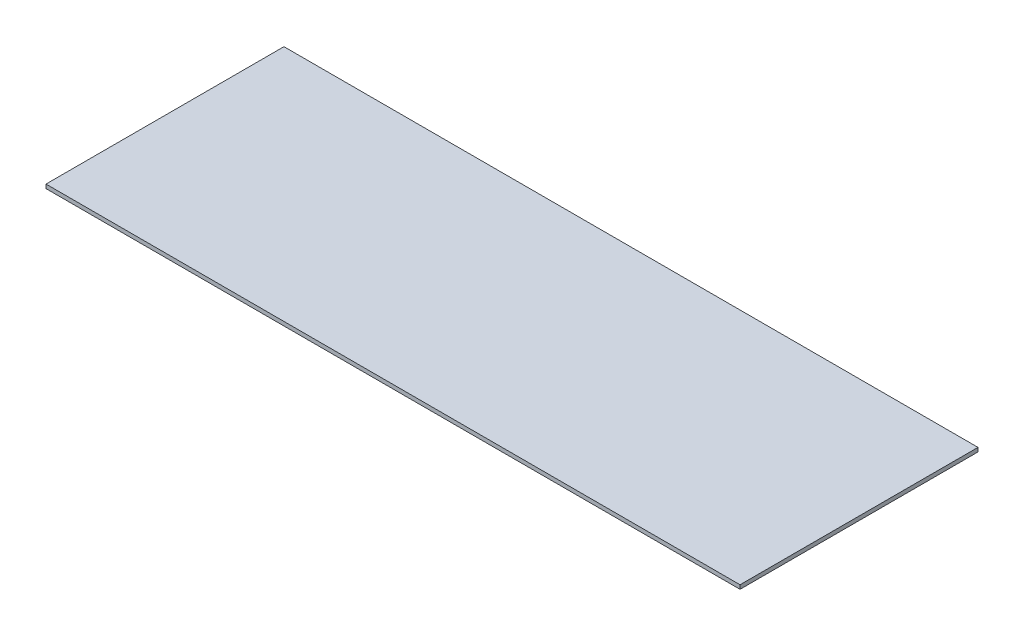
SolidWorks part; units mm, degrees
ref_plane "前视基准面" through (0, 0, 0) normal (0, 0, 1) x (1, 0, 0)
ref_plane "上视基准面" through (0, 0, 0) normal (0, 1, 0) x (1, 0, 0)
ref_plane "右视基准面" through (0, 0, 0) normal (1, 0, 0) x (0, 0, -1)
sketch "草图2" plane through (0, 0, 0) normal (0, 1, 0) x (1, 0, 0)
  line L1 (-192.809, 60.3371) -> (157.191, 60.3371)
  line L2 (-192.809, 60.3371) -> (-192.809, -59.6629)
  line L3 (-192.809, -59.6629) -> (157.191, -59.6629)
  line L4 (157.191, 60.3371) -> (157.191, -59.6629)
  point P4 (-278.764, 40.7865)
  point P5 (-272.6966, 105.5056)
  point P6 (0, 0)
  dimension "D1" = 120
  dimension "D2" = 350
extrude "凸台-拉伸2" add sketch "草图2" along normal blind 2 contours L4 L3 L2 L1
